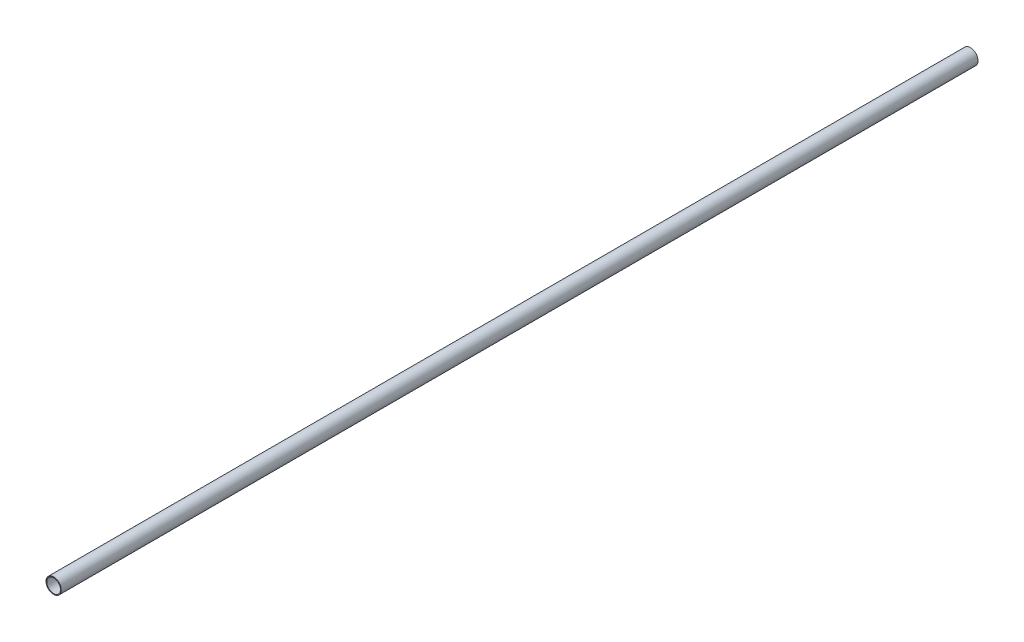
SolidWorks part; units mm, degrees
material "6061 Alloy"
ref_plane "Front Plane" through (0, 0, 0) normal (0, 0, 1) x (1, 0, 0)
ref_plane "Top Plane" through (0, 0, 0) normal (0, 1, 0) x (1, 0, 0)
ref_plane "Right Plane" through (0, 0, 0) normal (1, 0, 0) x (0, 0, -1)
sketch "Sketch1" plane through (0, 0, 0) normal (0, 0, 1) x (1, 0, 0)
  circle A0 centre (0, 0) radius 3.175
  circle A1 centre (0, 0) radius 2.8575
  dimension "D1" = 6.35
  dimension "D2" = 0.3175
extrude "Boss-Extrude1" add sketch "Sketch1" along normal blind 368.3 and the other way blind 12.7 contours A0 A1
